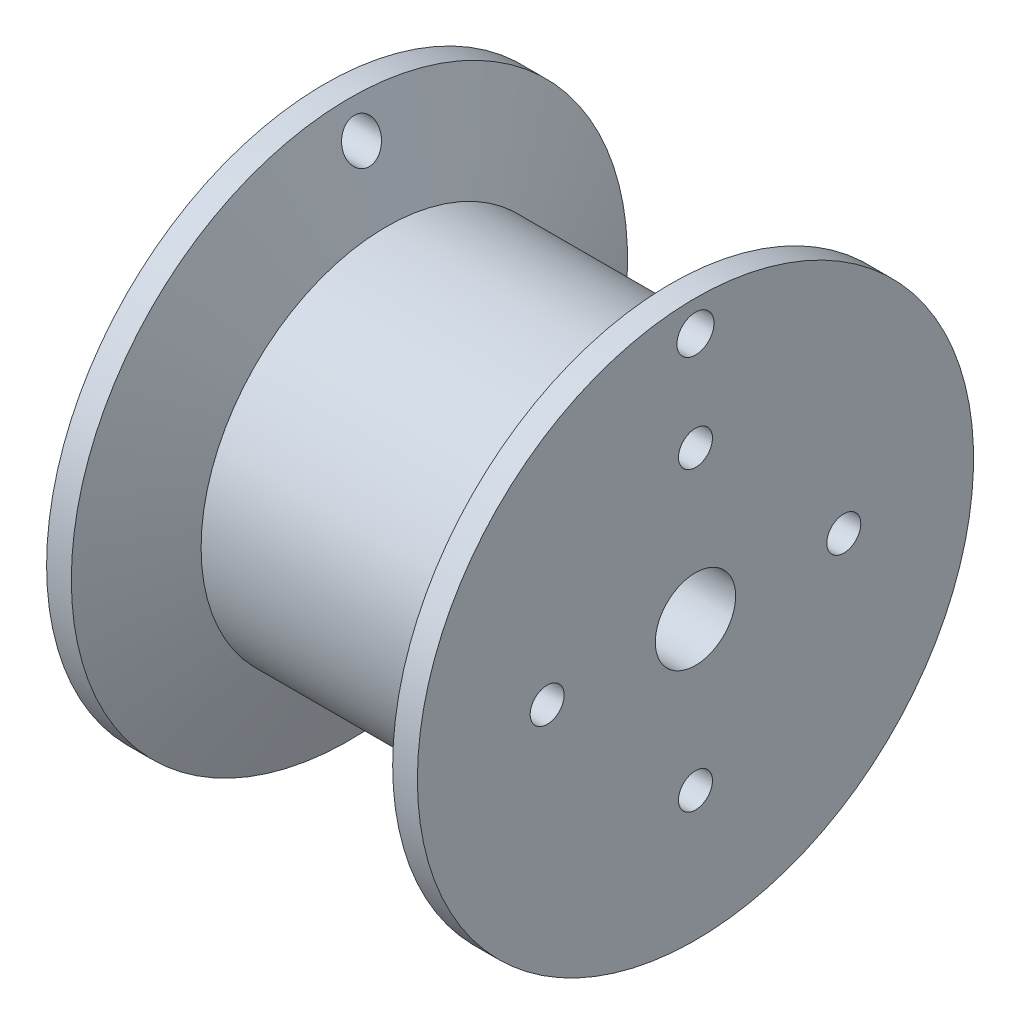
SolidWorks part; units mm, degrees
ref_plane "Front Plane" through (0, 0, 0) normal (0, 0, 1) x (1, 0, 0)
ref_plane "Top Plane" through (0, 0, 0) normal (0, 1, 0) x (1, 0, 0)
ref_plane "Right Plane" through (0, 0, 0) normal (1, 0, 0) x (0, 0, -1)
sketch "Sketch1" plane through (0, 0, 0) normal (0, 1, 0) x (1, 0, 0)
  line L0 (2, 22.5) -> (5, 15)
  line L1 (0, 0) -> (30, 0) construction
  line L2 (0, 0) -> (0, 22.5)
  line L3 (0, 22.5) -> (30, 22.5)
  line L4 (30, 0) -> (30, 22.5)
  line L5 (5, 15) -> (24.9959, 15)
  line L6 (24.9959, 15) -> (28, 22.5)
  line L8 (0, 0) -> (30, 0) construction
  line L9 (0, 0) -> (0, 3.25)
  line L10 (0, 3.25) -> (30, 3.25)
  line L11 (30, 0) -> (30, 3.25)
  dimension "D1" = 30
  dimension "D2" = 22.5
  dimension "D3" = 7.5
  dimension "D4" = 2
  dimension "D5" = 2
  dimension "D6" = 5.0041
  dimension "D7" = 5
  dimension "D8" = 3.25
revolve "Revolve1" add sketch "Sketch1" angle 360 about L1
sketch "Sketch2" plane through (30, 0, 0) normal (1, 0, 0) x (0, 0, -1)
  line L0 (0, 20) -> (0, 0) construction
  circle A0 centre (0, 0) radius 12 construction
  circle A1 centre (0, 12) radius 1.375
  circle A2 centre (0, 20) radius 1.5
  circle A3 centre (12, 0) radius 1.375
  circle A4 centre (0, -12) radius 1.375
  circle A5 centre (-12, 0) radius 1.375
  point P16 (0, 0)
  dimension "D1" = 24
  dimension "D2" = 2.75
  dimension "D3" = 3
  dimension "D4" = 20
  dimension "D5" = 4
extrude "Cut-Extrude1" cut sketch "Sketch2" against normal through all
